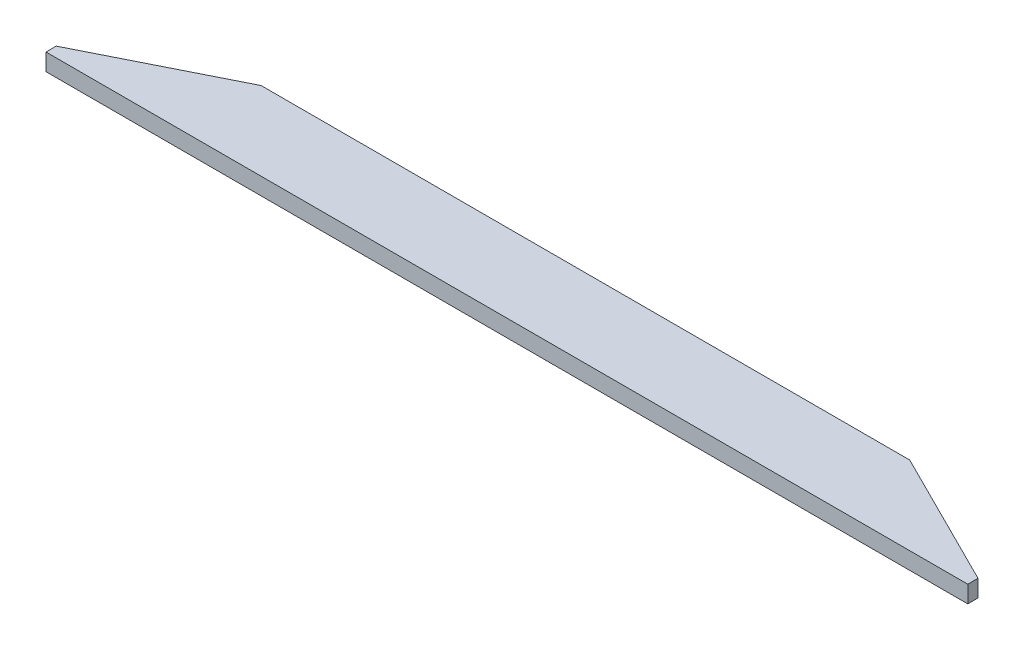
SolidWorks part; units mm, degrees
ref_plane "Plan de face" through (0, 0, 0) normal (0, 0, 1) x (1, 0, 0)
ref_plane "Plan de dessus" through (0, 0, 0) normal (0, 1, 0) x (1, 0, 0)
ref_plane "Plan de droite" through (0, 0, 0) normal (1, 0, 0) x (0, 0, -1)
sketch "Esquisse1" plane through (0, 0, 0) normal (0, 1, 0) x (1, 0, 0)
  line L1 (-135, 11.5) -> (135, 11.5)
  line L2 (-135, 11.5) -> (-135, -11.5)
  line L3 (-135, -11.5) -> (135, -11.5)
  line L4 (135, 11.5) -> (135, -11.5)
  line L5 (-135, 11.5) -> (135, -11.5) construction
  line L6 (-135, -11.5) -> (135, 11.5) construction
  point P0 (0, 0)
  dimension "D1" = 270
  dimension "D2" = 23
extrude "Boss.-Extru.1" add sketch "Esquisse1" along normal blind 5
sketch "Esquisse3" plane through (0, 5, 0) normal (0, 1, 0) x (1, 0, 0)
  line L0 (135, -8.5) -> (135, 11.5)
  line L1 (135, -11.5) -> (135, 11.5) construction
  line L2 (135, 11.5) -> (95, 11.5)
  line L3 (135, 11.5) -> (-135, 11.5) construction
  line L4 (95, 11.5) -> (135, -8.5)
  dimension "D1" = 40
  dimension "D2" = 20
extrude "Enlèv. mat.-Extru.1" cut sketch "Esquisse3" against normal blind 10
sketch "Esquisse5" plane through (0, 5, 0) normal (0, 1, 0) x (1, 0, 0)
  line L0 (-135, 11.5) -> (-95, 11.5)
  line L1 (95, 11.5) -> (-135, 11.5) construction
  line L2 (-95, 11.5) -> (-135, -8.5)
  line L3 (-135, 11.5) -> (-135, -11.5) construction
  line L4 (-135, -8.5) -> (-135, 11.5)
  dimension "D1" = 40
  dimension "D2" = 20
extrude "Enlèv. mat.-Extru.2" cut sketch "Esquisse5" against normal blind 10
